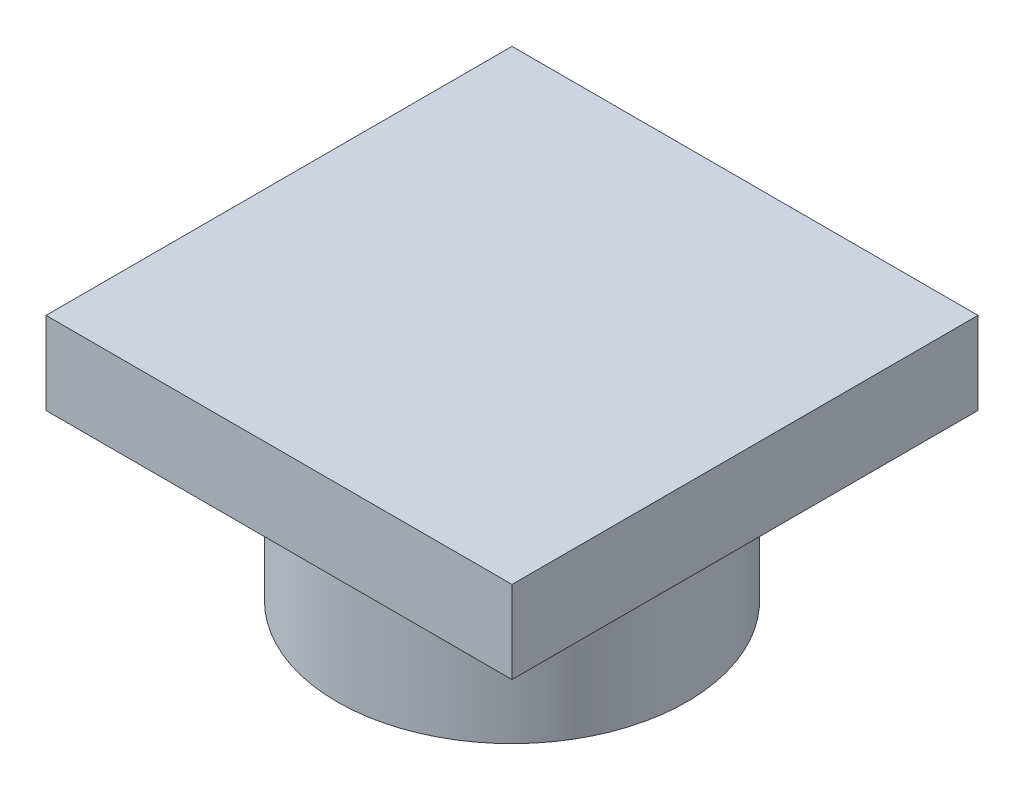
SolidWorks part; units mm, degrees
ref_plane "Front Plane" through (0, 0, 0) normal (0, 0, 1) x (1, 0, 0)
ref_plane "Top Plane" through (0, 0, 0) normal (0, 1, 0) x (1, 0, 0)
ref_plane "Right Plane" through (0, 0, 0) normal (1, 0, 0) x (0, 0, -1)
sketch "Sketch1" plane through (0, 0, 0) normal (0, 1, 0) x (1, 0, 0)
  circle A0 centre (0, 0) radius 4.25
  dimension "D1" = 8.5
extrude "Boss-Extrude1" add sketch "Sketch1" along normal blind 4
sketch "Sketch2" plane through (0, 4, 0) normal (0, 1, 0) x (1, 0, 0)
  line L0 (0, 0) -> (13.6781, 0)
  line L1 (-5.6569, 5.6569) -> (5.6569, 5.6569)
  line L2 (-5.6569, 5.6569) -> (-5.6569, -5.6569)
  line L3 (-5.6569, -5.6569) -> (5.6569, -5.6569)
  line L4 (5.6569, 5.6569) -> (5.6569, -5.6569)
  line L5 (-5.6569, 5.6569) -> (5.6569, -5.6569) construction
  line L6 (-5.6569, -5.6569) -> (5.6569, 5.6569) construction
  circle A0 centre (0, 0) radius 8
  dimension "D1" = 16
  dimension "D2" = 45
extrude "Boss-Extrude2" add sketch "Sketch2" along normal blind 2
